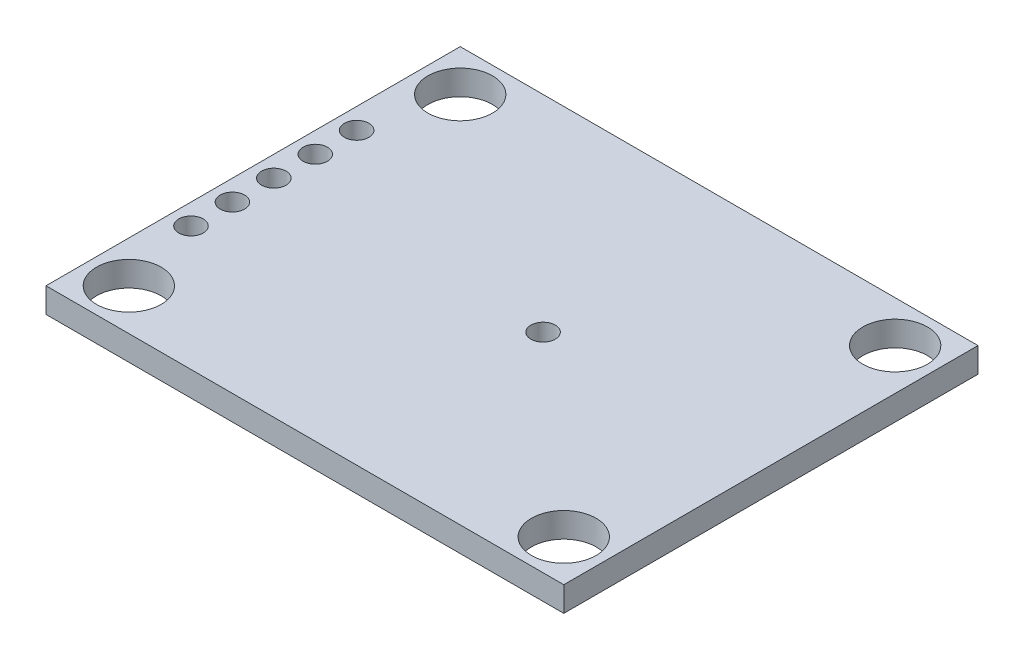
SolidWorks part; units mm, degrees
ref_plane "Front Plane" through (0, 0, 0) normal (0, 0, 1) x (1, 0, 0)
ref_plane "Top Plane" through (0, 0, 0) normal (0, 1, 0) x (1, 0, 0)
ref_plane "Right Plane" through (0, 0, 0) normal (1, 0, 0) x (0, 0, -1)
sketch "Sketch1" plane through (0, 0, 0) normal (0, 1, 0) x (1, 0, 0)
  line L1 (-15.875, -12.7) -> (15.875, -12.7)
  line L2 (-15.875, -12.7) -> (-15.875, 12.7)
  line L3 (-15.875, 12.7) -> (15.875, 12.7)
  line L4 (15.875, -12.7) -> (15.875, 12.7)
  line L5 (-15.875, -12.7) -> (15.875, 12.7) construction
  line L6 (-15.875, 12.7) -> (15.875, -12.7) construction
  point P0 (0, 0)
  dimension "D1" = 25.4
  dimension "D2" = 31.75
extrude "Boss-Extrude1" add sketch "Sketch1" along normal blind 1.524
sketch "Sketch2" plane through (0, 1.524, 0) normal (0, 1, 0) x (1, 0, 0)
  line L0 (0, 0) -> (0, 16.3069) construction
  line L1 (0, -0.8382) -> (0, 0.8382) construction
  line L2 (0, 0) -> (21.8501, 0) construction
  line L3 (-0.8382, 0) -> (0.8382, 0) construction
  circle A0 centre (-13.335, 10.16) radius 1.9812
  circle A1 centre (13.335, 10.16) radius 1.9812
  circle A2 centre (-13.335, -10.16) radius 1.9812
  circle A3 centre (13.335, -10.16) radius 1.9812
  dimension "D1" = 3.9624
  dimension "D2" = 20.32
  dimension "D3" = 26.67
extrude "Cut-Extrude1" cut sketch "Sketch2" against normal up to next
sketch "Sketch3" plane through (0, 1.524, 0) normal (0, 1, 0) x (1, 0, 0)
  line L0 (-15.875, 12.7) -> (-15.875, -12.7) construction
  line L1 (15.875, 12.7) -> (-15.875, 12.7) construction
  circle A0 centre (-14.605, 5.08) radius 0.75
  dimension "D1" = 1.5
  dimension "D2" = 1.27
  dimension "D3" = 7.62
extrude "Cut-Extrude2" cut sketch "Sketch3" against normal up to next
pattern_linear "LPattern1" count 5 spacing 2.54 along (0, 0, 1) of "Cut-Extrude2"
sketch "Sketch4" plane through (0, 1.524, 0) normal (0, 1, 0) x (1, 0, 0)
  line L0 (0, -0.8382) -> (0, 0.8382) construction
  line L1 (-0.8382, 0) -> (0.8382, 0) construction
  circle A0 centre (1.8288, 0.0762) radius 0.7493
  dimension "D1" = 1.4986
  dimension "D2" = 1.8288
  dimension "D3" = 0.0762
extrude "Cut-Extrude3" cut sketch "Sketch4" against normal up to next
